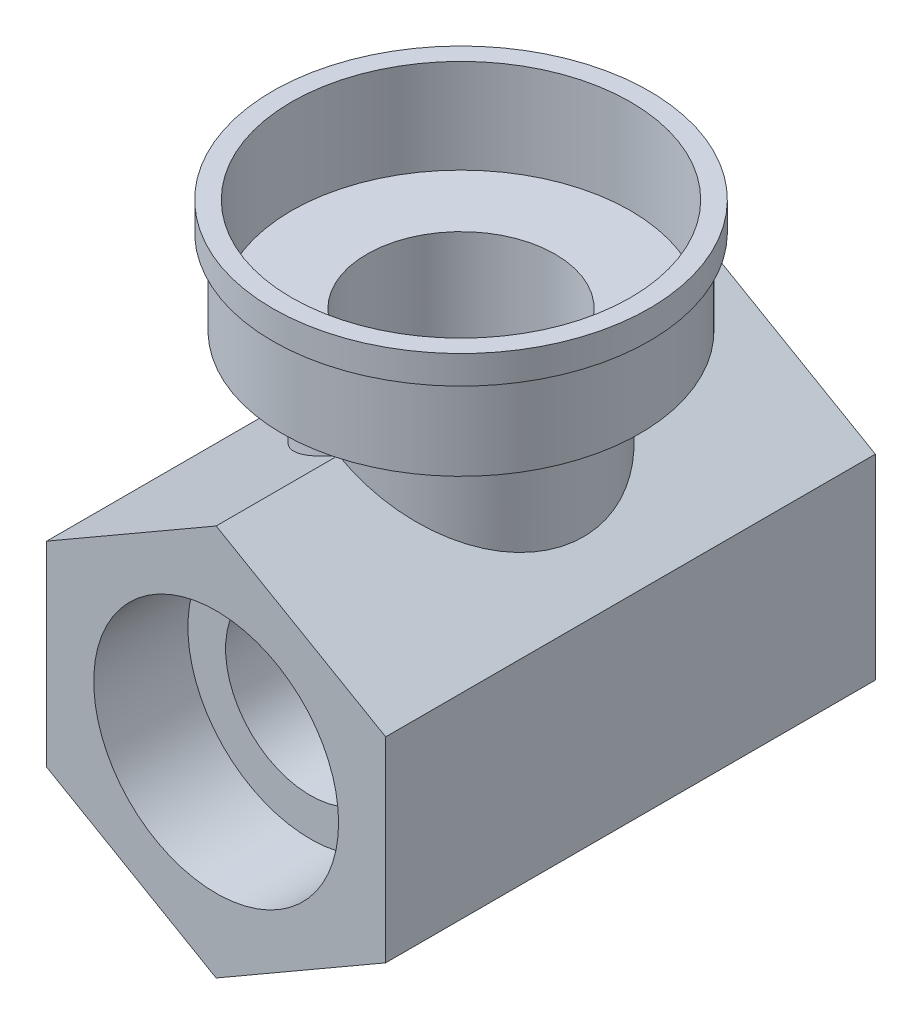
SolidWorks part; units mm, degrees
ref_plane "Front Plane" through (0, 0, 0) normal (0, 0, 1) x (1, 0, 0)
ref_plane "Top Plane" through (0, 0, 0) normal (0, 1, 0) x (1, 0, 0)
ref_plane "Right Plane" through (0, 0, 0) normal (1, 0, 0) x (0, 0, -1)
sketch "Sketch4" plane through (0, 0, 0) normal (0, 1, 0) x (1, 0, 0)
  circle A0 centre (0, 0) radius 20
  dimension "D1" = 40
extrude "Boss-Extrude2" add sketch "Sketch4" against normal blind 3
sketch "Sketch5" plane through (0, -3, 0) normal (0, -1, 0) x (1, 0, 0)
  circle A0 centre (0, 0) radius 19
  dimension "D1" = 38
extrude "Boss-Extrude3" add sketch "Sketch5" along normal blind 9
sketch "Sketch6" plane through (0, -12, 0) normal (0, -1, 0) x (1, 0, 0)
  circle A0 centre (0, 0) radius 13
  dimension "D1" = 26
extrude "Boss-Extrude4" add sketch "Sketch6" along normal blind 17
sketch "Sketch7" plane through (0, 0, 0) normal (0, 1, 0) x (1, 0, 0)
  circle A0 centre (0, 0) radius 18
  dimension "D1" = 36
extrude "Cut-Extrude3" cut sketch "Sketch7" against normal blind 10 contours A0
sketch "Sketch8" plane through (0, -29, 0) normal (0, -1, 0) x (1, 0, 0)
  circle A0 centre (0, 0) radius 10
  dimension "D1" = 20
extrude "Cut-Extrude4" cut sketch "Sketch8" against normal blind 19
sketch "Sketch9" plane through (0, 0, 0) normal (0, 0, 1) x (1, 0, 0)
  line L0 (0, -12) -> (0, -17) construction
  line L1 (-13, -12) -> (13, -12) construction
  line L9 (0, -17) -> (-18, -27.3923)
  line L10 (-18, -27.3923) -> (-18, -48.1769)
  line L11 (-18, -48.1769) -> (0, -58.5692)
  line L12 (0, -58.5692) -> (18, -48.1769)
  line L13 (18, -48.1769) -> (18, -27.3923)
  line L14 (18, -27.3923) -> (0, -17)
  circle A1 centre (0, -37.7846) radius 18 construction
  dimension "D2" = 36
  dimension "D1" = 5
extrude "Boss-Extrude5" add sketch "Sketch9" along normal mid plane 52
sketch "Sketch10" plane through (0, 0, 26) normal (0, 0, 1) x (1, 0, 0)
  circle A0 centre (0, -37.7846) radius 13
  dimension "D1" = 26
extrude "Cut-Extrude5" cut sketch "Sketch10" against normal blind 10
sketch "Sketch11" plane through (0, 0, 16) normal (0, 0, 1) x (1, 0, 0)
  circle A0 centre (0, -37.7846) radius 9
  dimension "D1" = 18
extrude "Cut-Extrude6" cut sketch "Sketch11" against normal blind 26
sketch "Sketch12" plane through (0, 0, -26) normal (0, 0, -1) x (-1, 0, 0)
  circle A0 centre (0, -37.7846) radius 13
  dimension "D1" = 26
extrude "Cut-Extrude7" cut sketch "Sketch12" against normal blind 10
sketch "Sketch13" plane through (0, 0, -16) normal (0, 0, -1) x (-1, 0, 0)
  circle A0 centre (0, -37.7846) radius 9
  dimension "D1" = 18
extrude "Cut-Extrude8" cut sketch "Sketch13" against normal blind 20
ref_plane "Plane1" through (0, -40, 0) normal (0, 1, 0) x (1, 0, 0)
sketch "Sketch30" plane through (0, 0, 0) normal (1, 0, 0) x (0, 0, -1)
  line L4 (-15.8266, -58.5109) -> (15.2981, -58.5109)
  arc A0 (-15.8266, -58.5109) -> (-10.3895, -55.6755) centre (-11.9202, -59.371) cw
  arc A1 (-10.3895, -55.6755) -> (10.3907, -55.4386) centre (-0.4867, -12.8043) ccw
  arc A2 (10.3907, -55.4386) -> (15.2981, -58.5109) centre (11.3796, -59.3144) cw
  dimension "D1" = 44
  dimension "D2" = 4
  dimension "D3" = 4
extrude "Cut-Extrude15" cut sketch "Sketch30" against normal mid plane 20.3
sketch "Sketch36" plane through (0, 0, 0) normal (1, 0, 0) x (0, 0, -1)
  line L0 (0, 0) -> (0, -58.5109) construction
  line L1 (-15.8266, -58.5109) -> (15.2981, -58.5109) construction
  line L2 (-7, -52.8015) -> (0, -52.8015)
  line L3 (-9, -28.7852) -> (-7, -49)
  line L4 (-10, -17) -> (0, -17)
  line L5 (0, -17) -> (0, -52.8015)
  line L6 (-10, -17) -> (-10, -27)
  line L7 (-10, -27) -> (-9, -28.7852)
  arc A0 (-7, -49) -> (-7, -52.8015) centre (-4.679, -50.9007) ccw
  ellipse E0 centre (0, -17) end of major axis (10, -17) minor radius 5.7735 (-10, -17) -> (10, -17) ccw construction
  dimension "D2" = 22
  dimension "D3" = 3
revolve "Cut-Revolve2" cut sketch "Sketch36" angle 360 about L5
